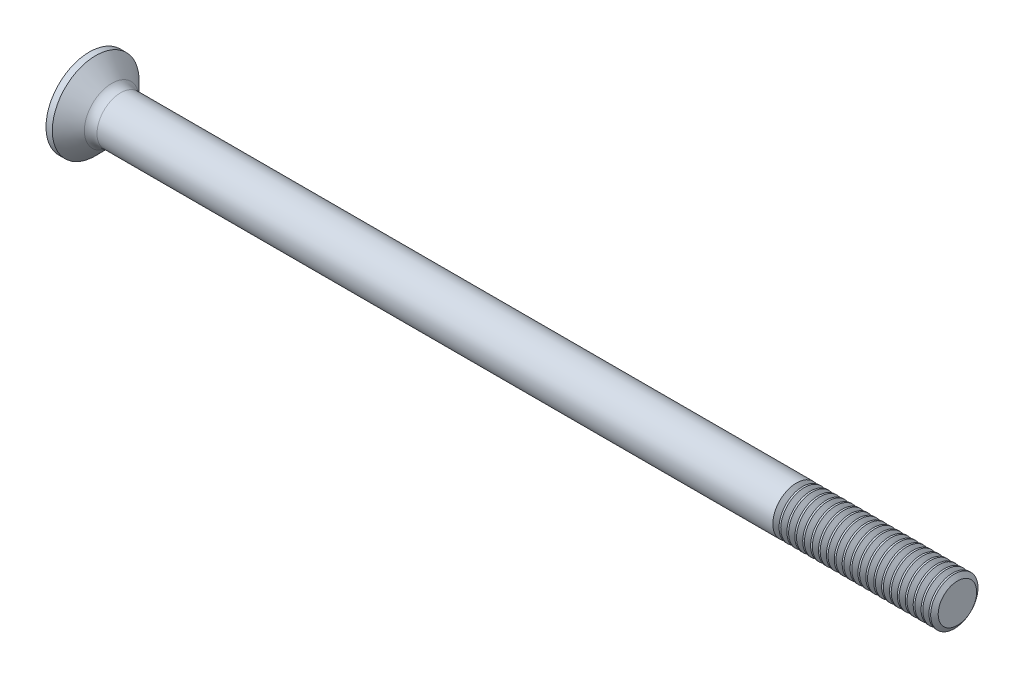
SolidWorks part; units mm, degrees
ref_plane "Plane1" through (0, 0, 0) normal (0, 0, 1) x (1, 0, 0)
ref_plane "Plane2" through (0, 0, 0) normal (0, 1, 0) x (1, 0, 0)
ref_plane "Plane3" through (0, 0, 0) normal (1, 0, 0) x (0, 0, -1)
sketch "BodySke" plane through (0, 0, 0) normal (0, 0, 1) x (1, 0, 0)
  line L0 (0, 0) -> (0, 2.75)
  line L1 (0, 2.75) -> (0.4, 2.75)
  line L2 (1.65, 1.5) -> (55, 1.5)
  line L3 (55, 1.5) -> (55, 0)
  line L4 (55, 0) -> (0, 0)
  line L5 (-6.35, 0) -> (82.55, 0) construction
  line L6 (1.65, -1.5) -> (55, -1.5) construction
  line L7 (0.4, -2.75) -> (1.65, -1.5) construction
  line L8 (0.4, 2.75) -> (1.65, 1.5)
  line L9 (0, -2.75) -> (0.4, -2.75) construction
  line L10 (2.15, 3.0875) -> (2.15, -6.4375) construction
  line L11 (45, 6.35) -> (45, -3.175) construction
  dimension "Diameter" = 3
  dimension "Length" = 55
  dimension "Head_ht" = 1.65
  dimension "Head_dia" = 5.5
  dimension "Head_ang" = 90
  dimension "D6" = 0.4
  dimension "Advance" = 0.5
  dimension "Thread_nom" = 10
revolve "Base-Revolve" add sketch "BodySke"
cosmetic thread "ThreadCosmetic" [suppressed]
fillet "Fillet1" radius 0.8 1 edges at (1.65, 0, 1.5)
sketch "Sketch3" plane through (0, 0, 0) normal (-1, 0, 0) x (0, 0, 1)
  line L0 (-0.37, 1.5) -> (0.37, 1.5)
  line L1 (0.37, 1.5) -> (0.37, -1.5)
  line L2 (0.37, -1.5) -> (-0.37, -1.5)
  line L3 (-0.37, -1.5) -> (-0.37, 1.5)
  dimension "D1" = 1.5
  dimension "Cross_dia" = 3
  dimension "D2" = 0.37
  dimension "Cross_width" = 0.74
ref_plane "Plane4" through (2.01, 0, 0) normal (-1, 0, 0) x (0, 0, 1)
sketch "Sketch4" plane through (2.01, 0, 0) normal (-1, 0, 0) x (0, 0, 1)
  line L0 (-0.37, 0.4979) -> (0.37, 0.4979)
  line L3 (0.37, 0.4979) -> (0.37, -0.4979)
  line L4 (0.37, -0.4979) -> (-0.37, -0.4979)
  line L5 (-0.37, -0.4979) -> (-0.37, 0.4979)
  dimension "D1" = 0.74
  dimension "D2" = 0.9957
  dimension "D3" = 0.37
  dimension "D4" = 0.4979
loft "Recess" cut profiles "Sketch3", "Sketch4"
pattern_circular "RecPat" count 2 every 90 about axis through (0, 0, 0) along (1, 0, 0) of "Recess"
sketch "RecCorSke" plane through (0, 0, 0) normal (0, 0, 1) x (1, 0, 0)
  line L0 (-3.175, 0) -> (15.875, 0) construction
  line L2 (0, 0) -> (0, 0.6966)
  line L3 (0, 0.6966) -> (2.01, 0.556)
  line L4 (2.01, 0.556) -> (2.1907, 0)
  line L5 (2.1907, 0) -> (0, 0)
  dimension "Diameter" = 1.112
  dimension "Depth" = 2.01
  dimension "Draft_angle" = 4
  dimension "Bottom_angle" = 18
revolve "RecessCore" cut sketch "RecCorSke" angle 360 about L0
sketch "ThdSchSke" plane through (0, 0, 0) normal (0, 0, 1) x (1, 0, 0)
  line L0 (45, -1.2195) -> (44.8036, -1.5)
  line L1 (45, -1.2195) -> (45.1964, -1.5)
  line L2 (45.1964, -1.5) -> (45.1964, -1.875)
  line L3 (-3.175, 0) -> (5.1513, 0) construction
  line L5 (45.1964, -1.875) -> (44.8036, -1.875)
  line L6 (44.8036, -1.875) -> (44.8036, -1.5)
  line L7 (0, 2.75) -> (0, -2.75) construction
  dimension "Thread_minor" = 2.439
  dimension "Diameter" = 3
  dimension "Start" = 45
  dimension "SideAngle" = 55
  dimension "VeeAngle" = 70
  dimension "Overcut" = 3.75
revolve "ThreadSchematic" cut sketch "ThdSchSke" angle 360 about L3
pattern_linear "ThdSchPat" count 21 spacing 0.5 along (1, 0, 0) of "ThreadSchematic"
equation "\"D1@Sketch3\" = \"Cross_dia@Sketch3\" / 2"
equation "\"D2@Sketch3\" = \"Cross_width@Sketch3\" / 2"
equation "\"Depth@RecCorSke\" = \"Cross_depth@Plane4\""
equation "\"D1@Sketch4\" = \"Cross_width@Sketch3\""
equation "\"D2@Sketch4\" = \"Cross_dia@Sketch3\" - 2.0 * \"Cross_depth@Plane4\" * tan(26.5  * 0.017453292)"
equation "\"D3@Sketch4\" = \"D1@Sketch4\" / 2"
equation "\"D4@Sketch4\" = \"D2@Sketch4\" / 2"
equation "\"Thread_length@ThreadCosmetic\" = ((sgn( (\"Length@BodySke\" - \"Advance@BodySke\" * 1.0 - \"Head_ht@BodySke\" ) - \"Thread_nom@BodySke\" )-1)*( (\"Length@BodySke\" - \"Advance@BodySke\" * 1.0 - \"Head_ht@BodySke\" ) - \"Thread_nom@BodySke\" ))/-2+ \"Thread_nom@BodySke\""
equation "\"Thread_minor@ThdSchSke\" = \"Thread_minor@ThreadCosmetic\""
equation "\"Diameter@ThdSchSke\" = \"Diameter@BodySke\""
equation "\"Overcut@ThdSchSke\" = \"Diameter@BodySke\" * 1.25"
equation "\"Start@ThdSchSke\" = 0.000001 + \"Length@BodySke\" - \"Thread_length@ThreadCosmetic\"  '---Countersunk---"
equation "\"Num_threads@ThdSchPat\" = int( \"Thread_length@ThreadCosmetic\" / \"Advance@BodySke\" + 0.999 )  + 1"
equation "\"Advance@ThdSchPat\" = \"Thread_length@ThreadCosmetic\" /  (\"Num_threads@ThdSchPat\" - 1) 'relax it"
